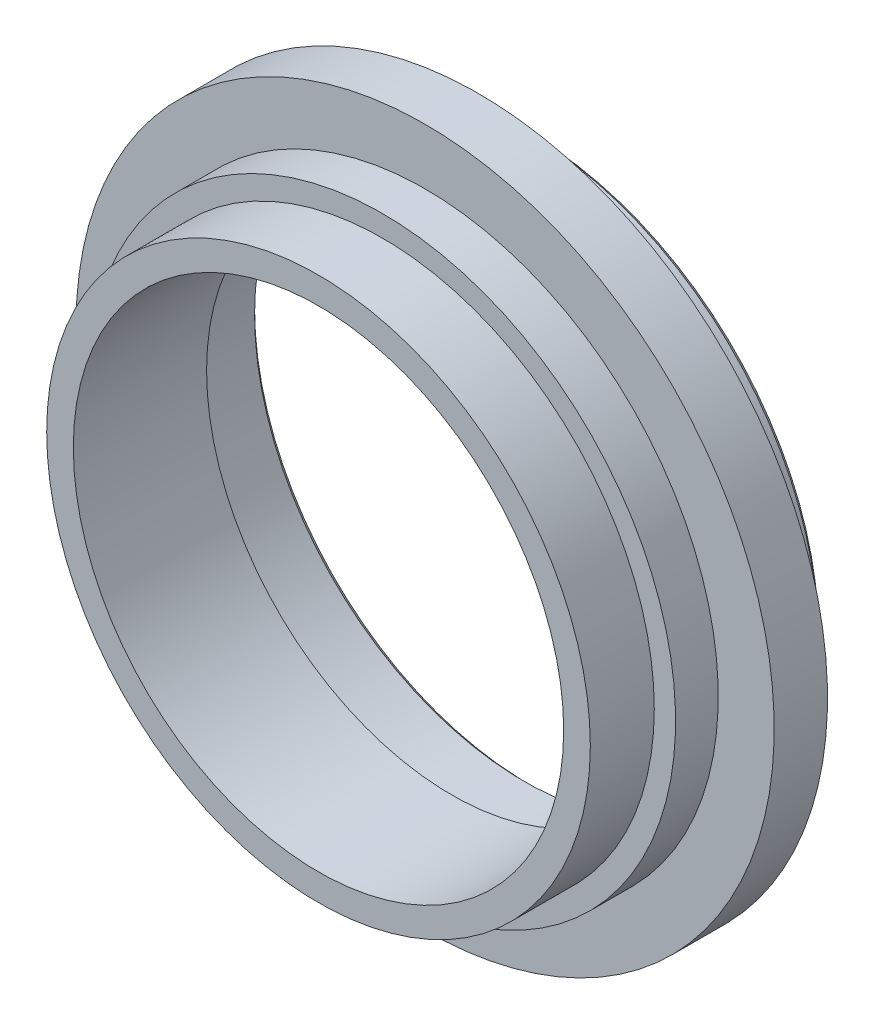
SolidWorks part; units mm, degrees
ref_plane "Front Plane" through (0, 0, 0) normal (0, 0, 1) x (1, 0, 0)
ref_plane "Top Plane" through (0, 0, 0) normal (0, 1, 0) x (1, 0, 0)
ref_plane "Right Plane" through (0, 0, 0) normal (1, 0, 0) x (0, 0, -1)
sketch "Sketch1" plane through (0, 0, 0) normal (0, 1, 0) x (1, 0, 0)
  line L0 (0, 99.2979) -> (0, -58.5521) construction
  line L1 (-100.4208, 0) -> (85.3417, 0) construction
  line L3 (25.3, 19.8) -> (27.6, 19.8)
  line L4 (27.6, 19.8) -> (27.6, 15)
  line L5 (27.6, 15) -> (32.75, 15)
  line L6 (32.75, 15) -> (32.75, 10)
  line L7 (32.75, 10) -> (27.5, 10)
  line L13 (25.5, 0) -> (23, 0)
  line L16 (25.3, 12.5) -> (23, 12.5)
  line L17 (23, 12.5) -> (23, 0)
  line L18 (25.3, 12.5) -> (25.3, 19.8)
  line L19 (25.5, 6) -> (27.5, 6)
  line L20 (27.5, 6) -> (27.5, 10)
  line L21 (25.5, 6) -> (25.5, 0)
  dimension "D2" = 2.3
  dimension "D3" = 32.75
  dimension "D4" = 25.5
  dimension "D5" = 2.5
  dimension "D6" = 4.8
  dimension "D7" = 5
  dimension "D8" = 19.8
  dimension "D9" = 6
  dimension "D13" = 2.5
  dimension "D14" = 25.3
  dimension "D16" = 27.5
revolve "Revolve1" add sketch "Sketch1" angle 360 about L0
chamfer "Chamfer1" distance 0.5 angle 45 2 edges at (-27.6, 0, -19.8) (-25.3, 0, -19.8)
